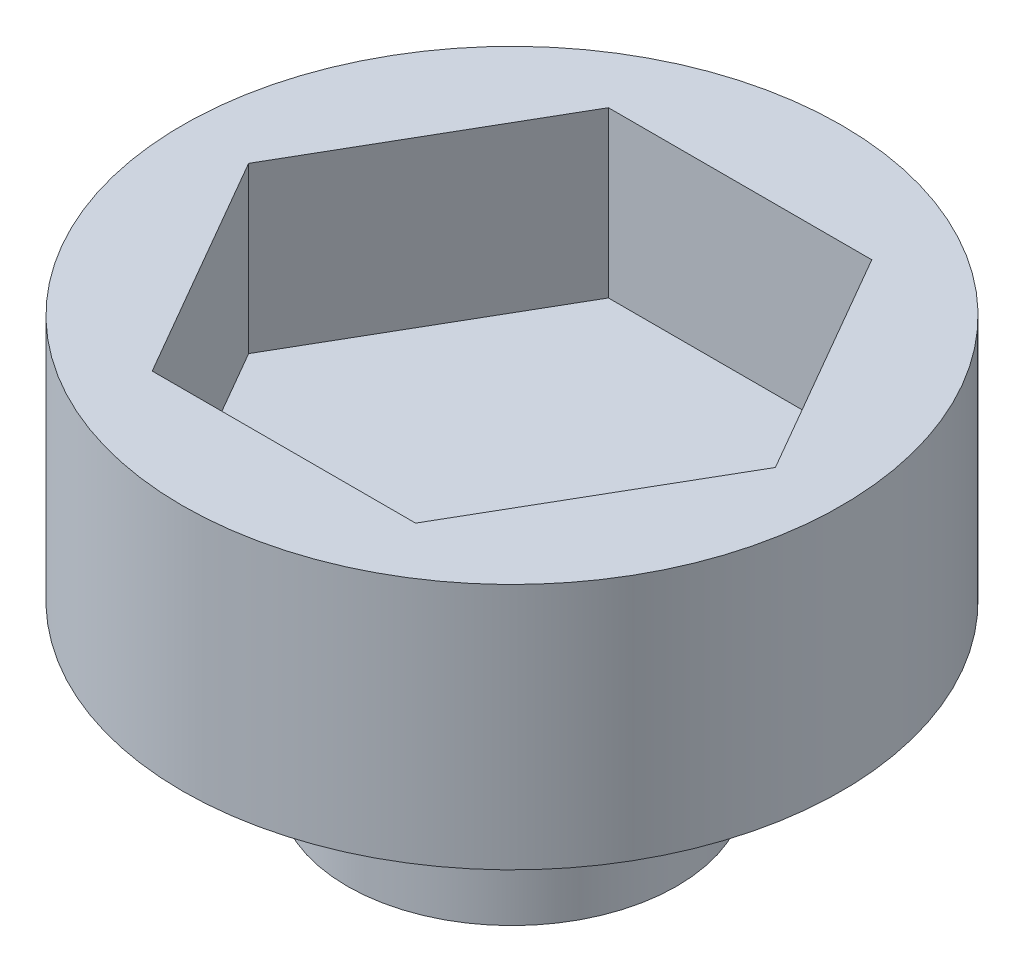
SolidWorks part; units mm, degrees
ref_plane "Front Plane" through (0, 0, 0) normal (0, 0, 1) x (1, 0, 0)
ref_plane "Top Plane" through (0, 0, 0) normal (0, 1, 0) x (1, 0, 0)
ref_plane "Right Plane" through (0, 0, 0) normal (1, 0, 0) x (0, 0, -1)
sketch "Sketch1" plane through (0, 0, 0) normal (0, 1, 0) x (1, 0, 0)
  circle A0 centre (0, 0) radius 2
  dimension "D1" = 4
extrude "Boss-Extrude1" add sketch "Sketch1" along normal blind 2
sketch "Sketch2" plane through (0, 2, 0) normal (0, 1, 0) x (1, 0, 0)
  circle A0 centre (0, 0) radius 4
  dimension "D1" = 8
extrude "Boss-Extrude2" add sketch "Sketch2" along normal blind 3
sketch "Sketch3" plane through (0, 5, 0) normal (0, 1, 0) x (1, 0, 0)
  line L1 (3.1967, 0) -> (1.5983, 2.7684)
  line L2 (1.5983, 2.7684) -> (-1.5983, 2.7684)
  line L3 (-1.5983, 2.7684) -> (-3.1967, 0)
  line L4 (-3.1967, 0) -> (-1.5983, -2.7684)
  line L5 (-1.5983, -2.7684) -> (1.5983, -2.7684)
  line L6 (1.5983, -2.7684) -> (3.1967, 0)
  circle A0 centre (0, 0) radius 2.7684 construction
extrude "Cut-Extrude1" cut sketch "Sketch3" against normal blind 2
